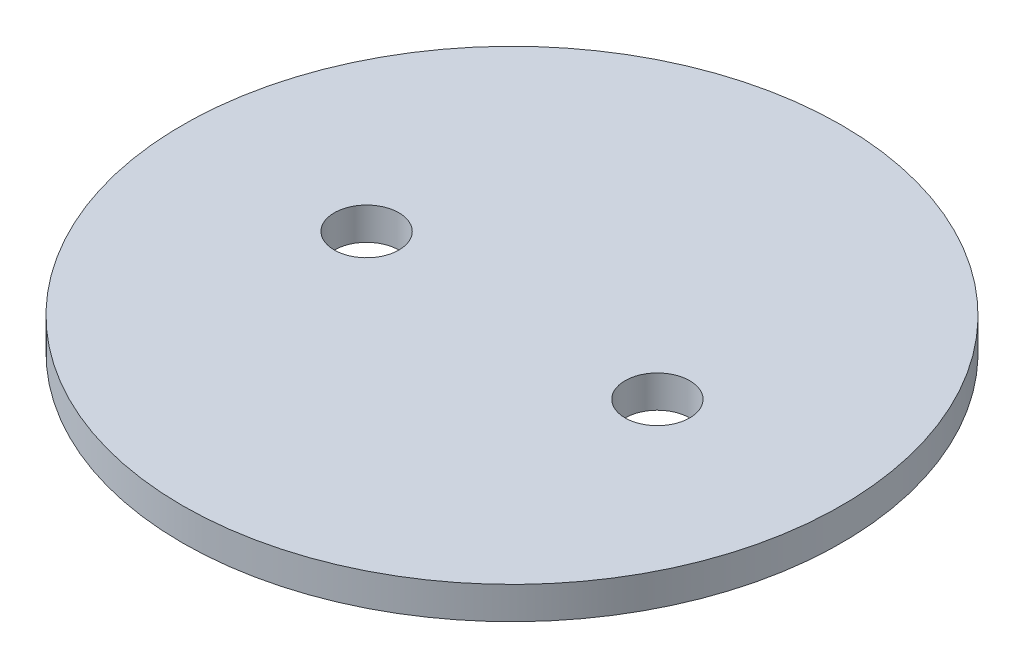
SolidWorks part; units mm, degrees
ref_plane "Спереди" through (0, 0, 0) normal (0, 0, 1) x (1, 0, 0)
ref_plane "Сверху" through (0, 0, 0) normal (0, 1, 0) x (1, 0, 0)
ref_plane "Справа" through (0, 0, 0) normal (1, 0, 0) x (0, 0, -1)
other "Configuration Table"
sketch "Эскиз1" plane through (0, 0, 0) normal (0, 1, 0) x (1, 0, 0)
  circle A0 centre (0, 0) radius 102
  circle A1 centre (-45, 0) radius 10
  circle A2 centre (45, 0) radius 10
  dimension "D1" = 204
  dimension "D2" = 45
  dimension "D3" = 45
extrude "Бобышка-Вытянуть1" add sketch "Эскиз1" along normal blind 10
